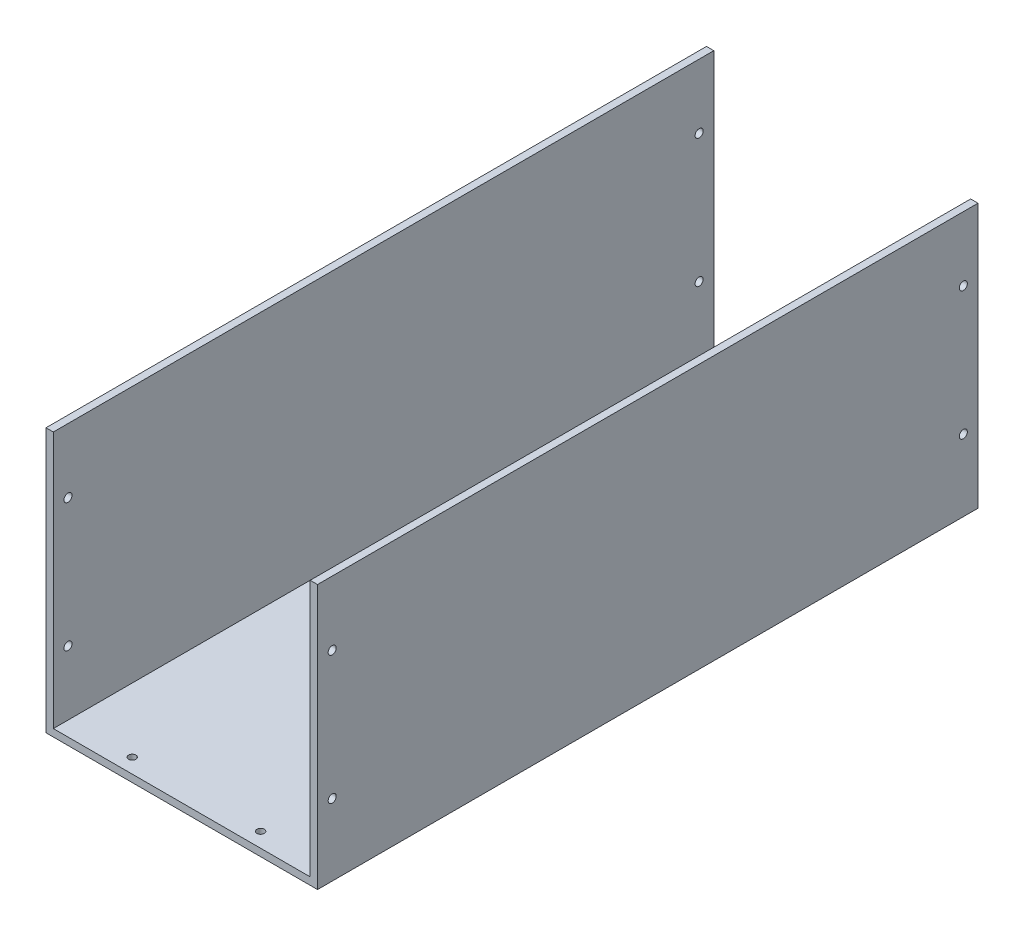
SolidWorks part; units mm, degrees
ref_plane "前视基准面" through (0, 0, 0) normal (0, 0, 1) x (1, 0, 0)
ref_plane "上视基准面" through (0, 0, 0) normal (0, 1, 0) x (1, 0, 0)
ref_plane "右视基准面" through (0, 0, 0) normal (1, 0, 0) x (0, 0, -1)
other "Configuration Table"
sketch "草图2" plane through (0, 0, 0) normal (0, 0, 1) x (1, 0, 0)
  line L0 (0, 109.5988) -> (0, -9.5909) construction
  line L1 (-35, 0) -> (35, 0)
  line L2 (35, 0) -> (35, 70)
  line L3 (-35, 0) -> (-35, 70)
  line L4 (37, -2) -> (37, 70)
  line L5 (-37, -2) -> (37, -2)
  line L6 (-37, -2) -> (-37, 70)
  line L7 (-37, 70) -> (-35, 70)
  line L8 (35, 70) -> (37, 70)
  dimension "D1" = 70
  dimension "D2" = 70
  dimension "D3" = 2
extrude "凸台-拉伸3" add sketch "草图2" along normal blind 180
sketch "草图3" plane through (37, 0, 0) normal (1, 0, 0) x (0, 0, -1)
  line L0 (0, 35) -> (13.2921, 35) construction
  line L1 (0, -2) -> (0, 70) construction
  circle A0 centre (-4, 52.5) radius 1.1
  circle A1 centre (-4, 17.5) radius 1.1
  dimension "D1" = 35
  dimension "D2" = 2.2
  dimension "D3" = 4
  dimension "D4" = 35
extrude "切除-拉伸1" cut sketch "草图3" against normal through all
ref_plane "基准面1" through (0, 0, 90) normal (0, 0, -1) x (-1, 0, 0)
mirror "镜向1" about plane through (0, 0, 90) normal (0, 0, -1) of "切除-拉伸1"
sketch "草图4" plane through (0, 0, 0) normal (0, 1, 0) x (1, 0, 0)
  line L0 (0, 10.3606) -> (0, -44.8533) construction
  line L1 (35, 0) -> (-35, 0) construction
  line L2 (39.6, -90) -> (-39.6, -90) construction
  circle A0 centre (-17.5, -4) radius 1
  circle A1 centre (17.5, -4) radius 1
  circle A2 centre (-17.5, -176) radius 1
  circle A3 centre (17.5, -176) radius 1
  dimension "D1" = 2
  dimension "D2" = 35
  dimension "D3" = 4
extrude "切除-拉伸2" cut sketch "草图4" against normal through all
